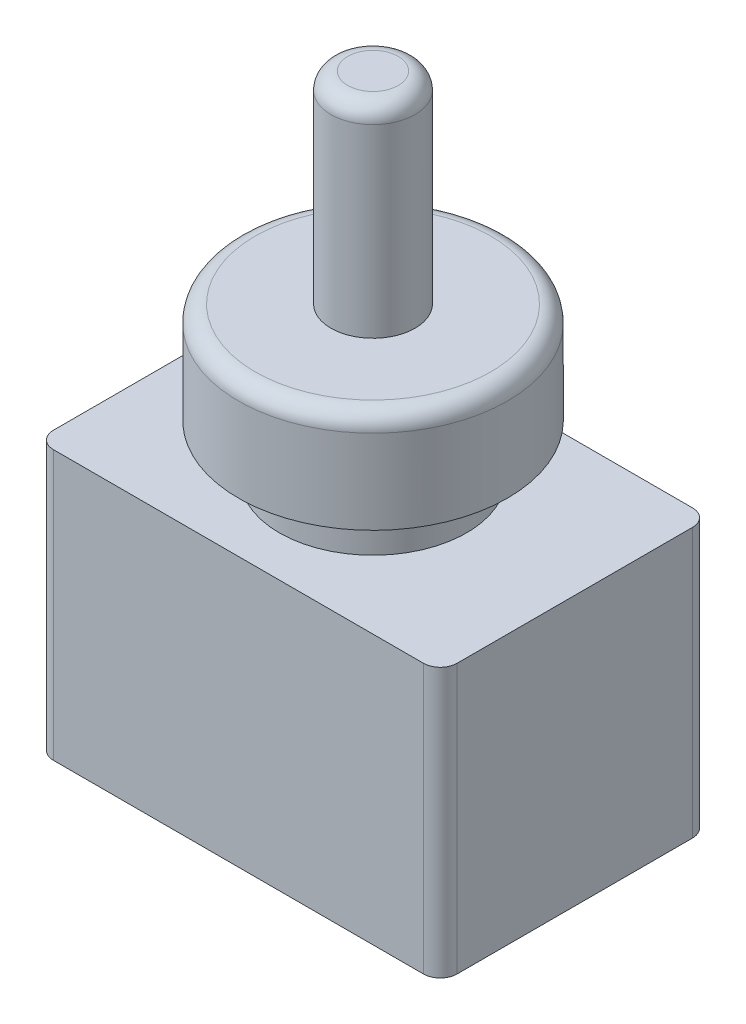
SolidWorks part; units mm, degrees
ref_plane "Front Plane" through (0, 0, 0) normal (0, 0, 1) x (1, 0, 0)
ref_plane "Top Plane" through (0, 0, 0) normal (0, 1, 0) x (1, 0, 0)
ref_plane "Right Plane" through (0, 0, 0) normal (1, 0, 0) x (0, 0, -1)
sketch "Sketch1" plane through (0, 0, 0) normal (0, 1, 0) x (1, 0, 0)
  line L1 (-12, 8) -> (12, 8)
  line L2 (-12, 8) -> (-12, -8)
  line L3 (-12, -8) -> (12, -8)
  line L4 (12, 8) -> (12, -8)
  line L5 (-12, 8) -> (12, -8) construction
  line L6 (-12, -8) -> (12, 8) construction
  point P0 (0, 0)
  dimension "D1" = 24
  dimension "D2" = 16
extrude "Boss-Extrude1" add sketch "Sketch1" along normal blind 16
sketch "Sketch2" plane through (0, 16, 0) normal (0, 1, 0) x (1, 0, 0)
  circle A0 centre (0, 0) radius 5.5719
extrude "Boss-Extrude2" add sketch "Sketch2" along normal blind 3
sketch "Sketch4" plane through (0, 0, 0) normal (0, 0, 1) x (1, 0, 0)
  line L0 (0, 0) -> (0, 37) construction
  line L1 (-12, 0) -> (12, 0) construction
  line L2 (0, 19) -> (8, 19)
  line L3 (5.5719, 19) -> (-5.5719, 19) construction
  line L4 (8, 19) -> (8, 25)
  line L5 (8, 25) -> (2.5, 25)
  line L6 (2.5, 25) -> (2.5, 37)
  line L7 (2.5, 37) -> (0, 37)
  line L8 (0, 19) -> (0, 37)
  dimension "D1" = 16
  dimension "D2" = 5
  dimension "D3" = 6
  dimension "D4" = 18
revolve "Revolve1" add sketch "Sketch4" angle 360 about L0
fillet "Fillet1" radius 1 1 edges at (8, 25, 0)
fillet "Fillet2" radius 1 1 edges at (2.5, 37, 0)
fillet "Fillet3" radius 1 4 edges at (12, 8, 8) (12, 8, -8) (-12, 8, -8) (-12, 8, 8)
equation "\"Mass Kg\"= \"SW-Mass\"*0.001"
